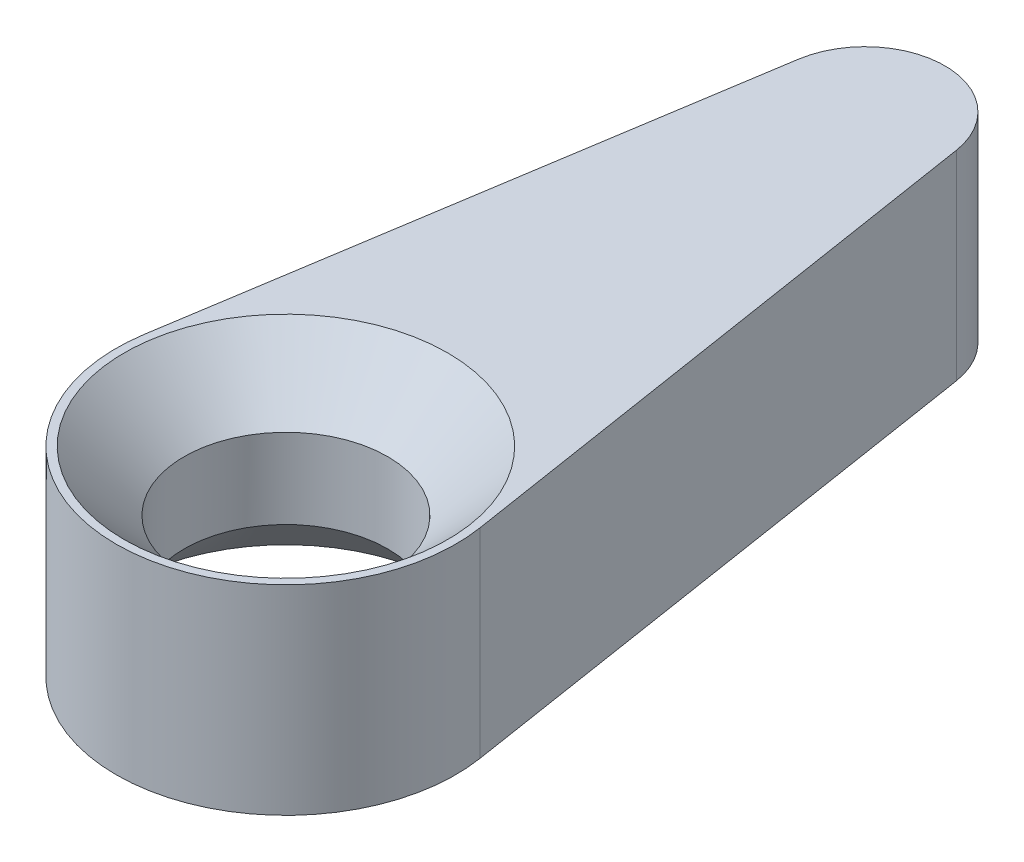
SolidWorks part; units mm, degrees
ref_plane "Front Plane" through (0, 0, 0) normal (0, 0, 1) x (1, 0, 0)
ref_plane "Top Plane" through (0, 0, 0) normal (0, 1, 0) x (1, 0, 0)
ref_plane "Right Plane" through (0, 0, 0) normal (1, 0, 0) x (0, 0, -1)
sketch "Sketch1" plane through (0, 0, 0) normal (0, 1, 0) x (1, 0, 0)
  line L0 (-10.6642, 1.6751) -> (-5.0185, 37.6183)
  line L1 (5.0185, 37.6183) -> (10.6642, 1.6751)
  circle A0 centre (0, 0) radius 6.477
  circle A1 centre (0, 0) radius 10.795
  arc A2 (-5.0185, 37.6183) -> (5.0185, 37.6183) centre (0, 36.83) cw
  dimension "D1" = 12.954
  dimension "D2" = 5.08
  dimension "D3" = 21.59
  dimension "D4" = 36.83
extrude "Boss-Extrude1" add sketch "Sketch1" along normal blind 12.7 contours A2 L0 A1 L1 | A1 A0
chamfer "Chamfer1" distance 3.81 angle 45 2 edges at (0, 12.7, 6.477) (0, 0, 6.477)
